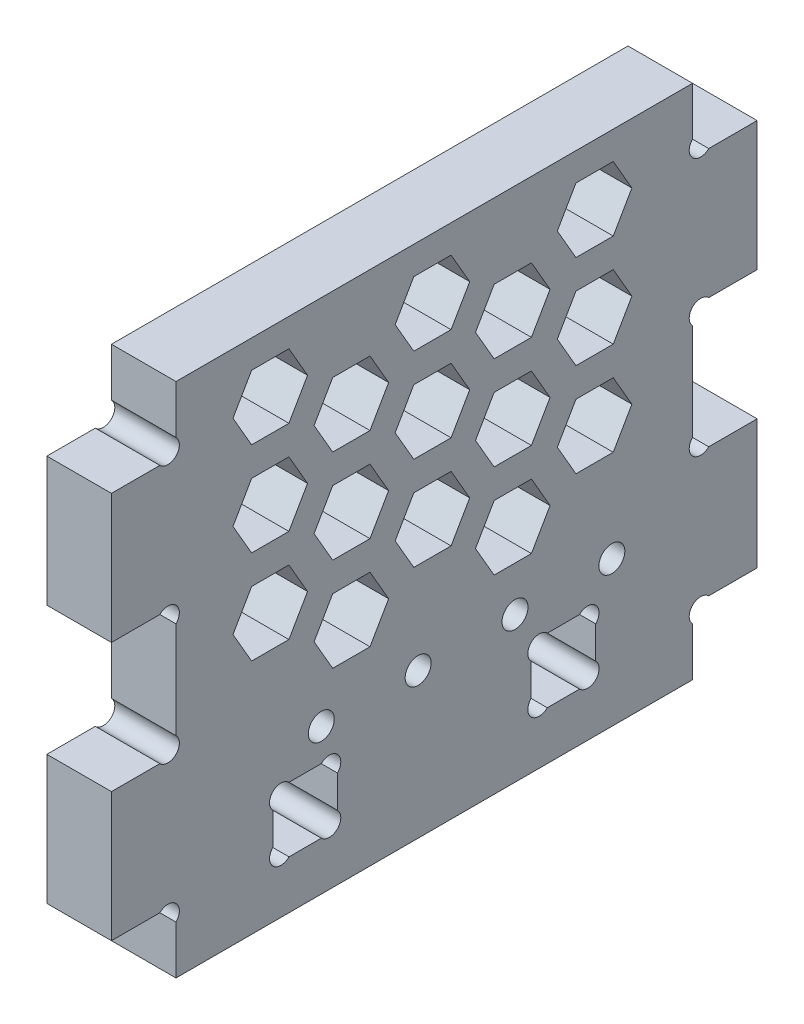
SolidWorks part; units mm, degrees
material "6061 Alloy"
ref_plane "Front" through (0, 0, 0) normal (0, 0, 1) x (1, 0, 0)
ref_plane "Top" through (0, 0, 0) normal (0, 1, 0) x (1, 0, 0)
ref_plane "Right" through (0, 0, 0) normal (1, 0, 0) x (0, 0, -1)
sketch "Sketch3" plane through (0, 0, 0) normal (1, 0, 0) x (0, 0, -1)
  line L1 (-50.8, -50.8) -> (50.8, -50.8)
  line L2 (-50.8, -50.8) -> (-50.8, 50.8)
  line L3 (-50.8, 50.8) -> (50.8, 50.8)
  line L4 (50.8, -50.8) -> (50.8, 50.8)
  line L5 (-50.8, -50.8) -> (50.8, 50.8) construction
  line L6 (-50.8, 50.8) -> (50.8, -50.8) construction
  point P0 (0, 0)
  dimension "D1" = 101.6
  dimension "D2" = 101.6
extrude "Square Extrusion" add sketch "Sketch3" along normal blind 12.7
sketch "Sketch4" plane through (12.7, 0, 0) normal (1, 0, 0) x (0, 0, -1)
  line L0 (-50.8, -50.8) -> (-25.4, -50.8) construction
  line L1 (-50.8, -50.8) -> (50.8, -50.8) construction
  line L2 (-25.4, -50.8) -> (-25.4, -34.925) construction
  line L3 (0, -50.8) -> (0, 50.8) construction
  line L4 (-31.75, -41.275) -> (-19.05, -41.275)
  line L5 (-31.75, -41.275) -> (-31.75, -28.575)
  line L6 (-31.75, -28.575) -> (-19.05, -28.575)
  line L7 (-19.05, -41.275) -> (-19.05, -28.575)
  line L8 (-31.75, -41.275) -> (-19.05, -28.575) construction
  line L9 (-31.75, -28.575) -> (-19.05, -41.275) construction
  line L10 (50.8, 50.8) -> (-50.8, 50.8) construction
  line L11 (31.75, -28.575) -> (19.05, -28.575)
  line L12 (19.05, -41.275) -> (19.05, -28.575)
  line L13 (31.75, -41.275) -> (19.05, -41.275)
  line L14 (31.75, -41.275) -> (31.75, -28.575)
  line L15 (-31.75, -34.925) -> (-19.05, -34.925) construction
  circle A0 centre (-20.6375, -30.1625) radius 2.2454
  circle A1 centre (-30.1625, -30.1625) radius 2.2454
  circle A2 centre (-20.6375, -39.6875) radius 2.2454
  circle A3 centre (-30.1625, -39.6875) radius 2.2454
  circle A4 centre (30.1625, -39.6875) radius 2.2454
  circle A5 centre (20.6375, -39.6875) radius 2.2454
  circle A6 centre (20.6375, -30.1625) radius 2.2454
  circle A7 centre (30.1625, -30.1625) radius 2.2454
  dimension "D7" = 4.4907
  dimension "D1" = 25.4
  dimension "D2" = 9.525
  dimension "D3" = 12.7
  dimension "D4" = 12.7
  dimension "D5" = 1.5875
extrude "Slotting Holes" cut sketch "Sketch4" against normal up to surface (12.7 mm away) contours A1 L5 L6 | A1 L6 L5 | A3 L4 A2 L7 A0 L6 A1 L5 | L6 A0 L7 | L7 A0 L6 | L4 A3 L5 | L5 A3 L4 | A2 L4 L7 | A2 L7 L4 | A6 L12 L11 | A6 L11 L12 | A7 L11 A6 L12 A5 L13 A4 L14 | L11 A7 L14 | L14 A7 L11 | A4 L13 L14 | A4 L14 L13 | L13 A5 L12 | L12 A5 L13 up to face at (0, 0, 0)
sketch "Sketch9" plane through (12.7, 0, 0) normal (1, 0, 0) x (0, 0, -1)
  line L96 (0, 0) -> (0, 11.43) construction
  line L97 (0, 6.985) -> (0, -6.985) construction
  line L111 (6.9677, 38.9312) -> (3.3015, 45.2812)
  line L112 (-24.9281, 38.9312) -> (-28.5942, 45.2812)
  line L113 (-28.5942, 45.2812) -> (-35.9266, 45.2812)
  line L114 (-35.9266, 45.2812) -> (-39.5928, 38.9312)
  line L115 (-39.5928, 38.9312) -> (-35.9266, 32.5812)
  line L116 (-35.9266, 32.5812) -> (-28.5942, 32.5812)
  line L117 (-28.5942, 32.5812) -> (-24.9281, 38.9312)
  line L118 (3.3015, 45.2812) -> (-4.0309, 45.2812)
  line L119 (-4.0309, 45.2812) -> (-7.697, 38.9312)
  line L120 (-7.697, 38.9312) -> (-4.0309, 32.5812)
  line L121 (-4.0309, 32.5812) -> (3.3015, 32.5812)
  line L122 (3.3015, 32.5812) -> (6.9677, 38.9312)
  line L123 (38.8634, 38.9312) -> (35.1972, 45.2812)
  line L124 (35.1972, 45.2812) -> (27.8648, 45.2812)
  line L125 (27.8648, 45.2812) -> (24.1987, 38.9312)
  line L126 (24.1987, 38.9312) -> (27.8648, 32.5812)
  line L127 (27.8648, 32.5812) -> (35.1972, 32.5812)
  line L128 (35.1972, 32.5812) -> (38.8634, 38.9312)
  line L129 (-8.9802, 29.7237) -> (-12.6464, 36.0737)
  line L130 (-12.6464, 36.0737) -> (-19.9787, 36.0737)
  line L131 (-19.9787, 36.0737) -> (-23.6449, 29.7237)
  line L132 (-23.6449, 29.7237) -> (-19.9787, 23.3737)
  line L133 (-19.9787, 23.3737) -> (-12.6464, 23.3737)
  line L134 (-12.6464, 23.3737) -> (-8.9802, 29.7237)
  line L135 (22.7698, 29.7237) -> (19.1036, 36.0737)
  line L136 (19.1036, 36.0737) -> (11.7713, 36.0737)
  line L137 (11.7713, 36.0737) -> (8.1051, 29.7237)
  line L138 (8.1051, 29.7237) -> (11.7713, 23.3737)
  line L139 (11.7713, 23.3737) -> (19.1036, 23.3737)
  line L140 (19.1036, 23.3737) -> (22.7698, 29.7237)
  line L141 (-24.9281, 20.5162) -> (-28.5942, 26.8662)
  line L142 (-28.5942, 26.8662) -> (-35.9266, 26.8662)
  line L143 (-35.9266, 26.8662) -> (-39.5928, 20.5162)
  line L144 (-39.5928, 20.5162) -> (-35.9266, 14.1662)
  line L145 (-35.9266, 14.1662) -> (-28.5942, 14.1662)
  line L146 (-28.5942, 14.1662) -> (-24.9281, 20.5162)
  line L147 (6.9677, 20.5162) -> (3.3015, 26.8662)
  line L148 (3.3015, 26.8662) -> (-4.0309, 26.8662)
  line L149 (-4.0309, 26.8662) -> (-7.697, 20.5162)
  line L150 (-7.697, 20.5162) -> (-4.0309, 14.1662)
  line L151 (-4.0309, 14.1662) -> (3.3015, 14.1662)
  line L152 (3.3015, 14.1662) -> (6.9677, 20.5162)
  line L153 (38.8634, 20.5162) -> (35.1972, 26.8662)
  line L154 (35.1972, 26.8662) -> (27.8648, 26.8662)
  line L155 (27.8648, 26.8662) -> (24.1987, 20.5162)
  line L156 (24.1987, 20.5162) -> (27.8648, 14.1662)
  line L157 (27.8648, 14.1662) -> (35.1972, 14.1662)
  line L158 (35.1972, 14.1662) -> (38.8634, 20.5162)
  line L159 (-24.9281, 2.1012) -> (-28.5942, 8.4512)
  line L160 (-28.5942, 8.4512) -> (-35.9266, 8.4512)
  line L161 (-35.9266, 8.4512) -> (-39.5928, 2.1012)
  line L162 (-39.5928, 2.1012) -> (-35.9266, -4.2488)
  line L163 (-35.9266, -4.2488) -> (-28.5942, -4.2488)
  line L164 (-28.5942, -4.2488) -> (-24.9281, 2.1012)
  line L165 (-8.9802, -7.1063) -> (-12.6464, -0.7563)
  line L166 (-12.6464, -0.7563) -> (-19.9787, -0.7563)
  line L167 (-19.9787, -0.7563) -> (-23.6449, -7.1063)
  line L168 (-23.6449, -7.1063) -> (-19.9787, -13.4563)
  line L169 (-19.9787, -13.4563) -> (-12.6464, -13.4563)
  line L170 (-12.6464, -13.4563) -> (-8.9802, -7.1063)
  line L171 (6.9677, 2.1012) -> (3.3015, 8.4512)
  line L172 (3.3015, 8.4512) -> (-4.0309, 8.4512)
  line L173 (-4.0309, 8.4512) -> (-7.697, 2.1012)
  line L174 (-7.697, 2.1012) -> (-4.0309, -4.2488)
  line L175 (-4.0309, -4.2488) -> (3.3015, -4.2488)
  line L176 (3.3015, -4.2488) -> (6.9677, 2.1012)
  line L177 (22.7698, -7.1063) -> (19.1036, -0.7563)
  line L178 (19.1036, -0.7563) -> (11.7713, -0.7563)
  line L179 (11.7713, -0.7563) -> (8.1051, -7.1063)
  line L180 (8.1051, -7.1063) -> (11.7713, -13.4563)
  line L181 (11.7713, -13.4563) -> (19.1036, -13.4563)
  line L182 (19.1036, -13.4563) -> (22.7698, -7.1063)
  line L183 (38.8634, 2.1012) -> (35.1972, 8.4512)
  line L184 (35.1972, 8.4512) -> (27.8648, 8.4512)
  line L185 (27.8648, 8.4512) -> (24.1987, 2.1012)
  line L186 (24.1987, 2.1012) -> (27.8648, -4.2488)
  line L187 (27.8648, -4.2488) -> (35.1972, -4.2488)
  line L188 (35.1972, -4.2488) -> (38.8634, 2.1012)
  line L189 (38.8634, -16.3138) -> (35.1972, -9.9638)
  line L190 (35.1972, -9.9638) -> (27.8648, -9.9638)
  line L191 (27.8648, -9.9638) -> (24.1987, -16.3138)
  line L192 (24.1987, -16.3138) -> (27.8648, -22.6638)
  line L193 (27.8648, -22.6638) -> (35.1972, -22.6638)
  line L194 (35.1972, -22.6638) -> (38.8634, -16.3138)
  line L195 (6.9677, -16.3138) -> (3.3015, -9.9638)
  line L196 (-4.0309, -9.9638) -> (-7.697, -16.3138)
  line L197 (-7.697, -16.3138) -> (-4.0309, -22.6638)
  line L198 (-4.0309, -22.6638) -> (3.3015, -22.6638)
  line L199 (3.3015, -22.6638) -> (6.9677, -16.3138)
  line L200 (3.3015, -9.9638) -> (-4.0309, -9.9638)
  line L201 (-24.9281, -16.3138) -> (-28.5942, -9.9638)
  line L202 (-28.5942, -9.9638) -> (-35.9266, -9.9638)
  line L203 (-35.9266, -9.9638) -> (-39.5928, -16.3138)
  line L204 (-39.5928, -16.3138) -> (-35.9266, -22.6638)
  line L205 (-35.9266, -22.6638) -> (-28.5942, -22.6638)
  line L206 (-28.5942, -22.6638) -> (-24.9281, -16.3138)
  line L207 (22.7698, 11.3087) -> (19.1036, 17.6587)
  line L208 (19.1036, 17.6587) -> (11.7713, 17.6587)
  line L209 (11.7713, 17.6587) -> (8.1051, 11.3087)
  line L210 (8.1051, 11.3087) -> (11.7713, 4.9587)
  line L211 (11.7713, 4.9587) -> (19.1036, 4.9587)
  line L212 (19.1036, 4.9587) -> (22.7698, 11.3087)
  line L213 (-8.9802, 11.3087) -> (-12.6464, 17.6587)
  line L214 (-12.6464, 17.6587) -> (-19.9787, 17.6587)
  line L215 (-19.9787, 17.6587) -> (-23.6449, 11.3087)
  line L216 (-23.6449, 11.3087) -> (-19.9787, 4.9587)
  line L217 (-19.9787, 4.9587) -> (-12.6464, 4.9587)
  line L218 (-12.6464, 4.9587) -> (-8.9802, 11.3087)
  circle A0 centre (-32.2604, 38.9312) radius 6.35 construction
  circle A1 centre (-0.3647, 38.9312) radius 6.35 construction
  circle A2 centre (31.531, 38.9312) radius 6.35 construction
  circle A3 centre (-16.3126, 29.7237) radius 6.35 construction
  circle A4 centre (15.4374, 29.7237) radius 6.35 construction
  circle A5 centre (-32.2604, 20.5162) radius 6.35 construction
  circle A6 centre (-0.3647, 20.5162) radius 6.35 construction
  circle A7 centre (31.531, 20.5162) radius 6.35 construction
  circle A8 centre (-32.2604, 2.1012) radius 6.35 construction
  circle A9 centre (-16.3126, -7.1063) radius 6.35 construction
  circle A10 centre (-0.3647, 2.1012) radius 6.35 construction
  circle A11 centre (15.4374, -7.1063) radius 6.35 construction
  circle A12 centre (31.531, 2.1012) radius 6.35 construction
  circle A13 centre (31.531, -16.3138) radius 6.35 construction
  circle A14 centre (-0.3647, -16.3138) radius 6.35 construction
  circle A15 centre (-32.2604, -16.3138) radius 6.35 construction
  circle A16 centre (-16.3126, 11.3087) radius 6.35 construction
  circle A17 centre (15.4374, 11.3087) radius 6.35 construction
  dimension "D1" = 11.43
extrude "Honeycomb Pocketing" cut sketch "Sketch9" against normal up to surface (12.7 mm away) contours L116 L117 L112 L113 L114 L115 | L121 L122 L111 L118 L119 L120 | L127 L128 L123 L124 L125 L126 | L133 L134 L129 L130 L131 L132 | L139 L140 L135 L136 L137 L138 | L157 L158 L153 L154 L155 L156 | L151 L152 L147 L148 L149 L150 | L145 L146 L141 L142 L143 L144 | L217 L218 L213 L214 L215 L216 | L211 L212 L207 L208 L209 L210 | L163 L164 L159 L160 L161 L162 | L175 L176 L171 L172 L173 L174 | L187 L188 L183 L184 L185 L186 | L169 L170 L165 L166 L167 L168 | L181 L182 L177 L178 L179 L180 up to face at (0, -34.925, 25.4)
sketch "Sketch10" plane through (12.7, 0, 0) normal (1, 0, 0) x (0, 0, -1)
  line L0 (-50.8, 0) -> (50.8, 0) construction
  line L1 (-50.8, 0) -> (-50.8, 50.8) construction
  line L2 (-50.8, 25.4) -> (-63.5, 25.4)
  line L3 (-50.8, 25.4) -> (-50.8, 38.1)
  line L4 (-50.8, 38.1) -> (-63.5, 38.1)
  line L5 (-63.5, 25.4) -> (-63.5, 38.1)
  line L6 (-63.5, 25.4) -> (-50.8, 25.4)
  line L7 (-63.5, 25.4) -> (-63.5, 12.7)
  line L8 (-63.5, 12.7) -> (-50.8, 12.7)
  line L9 (-50.8, 25.4) -> (-50.8, 12.7)
  line L10 (50.8, -50.8) -> (50.8, 50.8) construction
  line L11 (-63.5, -12.7) -> (-50.8, -12.7)
  line L12 (-50.8, -25.4) -> (-50.8, -12.7)
  line L13 (-63.5, -25.4) -> (-50.8, -25.4)
  line L14 (-63.5, -25.4) -> (-63.5, -12.7)
  line L15 (-50.8, -38.1) -> (-63.5, -38.1)
  line L16 (-63.5, -25.4) -> (-63.5, -38.1)
  line L17 (-50.8, -25.4) -> (-63.5, -25.4)
  line L18 (-50.8, -25.4) -> (-50.8, -38.1)
  line L19 (0, 50.8) -> (0, -50.8) construction
  line L20 (50.8, 50.8) -> (-50.8, 50.8) construction
  line L21 (-50.8, -50.8) -> (50.8, -50.8) construction
  line L22 (50.8, -38.1) -> (63.5, -38.1)
  line L23 (63.5, -25.4) -> (63.5, -38.1)
  line L24 (63.5, -25.4) -> (50.8, -25.4)
  line L25 (63.5, -25.4) -> (63.5, -12.7)
  line L26 (63.5, -12.7) -> (50.8, -12.7)
  line L27 (50.8, -25.4) -> (50.8, -12.7)
  line L28 (50.8, -25.4) -> (50.8, -38.1)
  line L29 (63.5, 12.7) -> (50.8, 12.7)
  line L30 (50.8, 25.4) -> (50.8, 12.7)
  line L31 (63.5, 25.4) -> (50.8, 25.4)
  line L32 (63.5, 25.4) -> (63.5, 12.7)
  line L33 (50.8, 38.1) -> (63.5, 38.1)
  line L34 (63.5, 25.4) -> (63.5, 38.1)
  line L35 (50.8, 25.4) -> (63.5, 25.4)
  line L36 (50.8, 25.4) -> (50.8, 38.1)
  line L37 (-63.5, 38.1) -> (-50.8, 38.1)
  line L43 (-63.5, 12.7) -> (-50.8, 12.7)
  line L44 (-53.9752, 41.2752) -> (-50.8, 38.1) construction
  line L46 (-50.8, 41.2754) -> (-50.8, 38.1)
  line L47 (-50.8, 12.7) -> (-50.8, 9.5246)
  line L48 (-50.8, -9.5246) -> (-50.8, -12.7)
  line L49 (-50.8, 50.8) -> (-50.8, -50.8) construction
  line L50 (-50.8, -41.2754) -> (-50.8, -38.1)
  line L51 (50.8, -41.2754) -> (50.8, -38.1)
  line L52 (50.8, -9.5246) -> (50.8, -12.7)
  line L53 (50.8, 12.7) -> (50.8, 9.5246)
  line L54 (50.8, 41.2754) -> (50.8, 38.1)
  arc A2 (-53.9754, 38.1) -> (-50.8, 41.2754) centre (-52.3877, 39.6877) ccw
  arc A5 (-53.9754, 12.7) -> (-50.8, 9.5246) centre (-52.3877, 11.1123) cw
  arc A8 (53.9754, 12.7) -> (50.8, 9.5246) centre (52.3877, 11.1123) ccw
  arc A9 (53.9754, 38.1) -> (50.8, 41.2754) centre (52.3877, 39.6877) cw
  arc A10 (53.9754, -12.7) -> (50.8, -9.5246) centre (52.3877, -11.1123) cw
  arc A11 (53.9754, -38.1) -> (50.8, -41.2754) centre (52.3877, -39.6877) ccw
  arc A12 (-53.9754, -12.7) -> (-50.8, -9.5246) centre (-52.3877, -11.1123) ccw
  arc A13 (-53.9754, -38.1) -> (-50.8, -41.2754) centre (-52.3877, -39.6877) cw
  point P43 (50.8, 50.8)
  point P68 (0, 0)
  dimension "D4" = 12.7
  dimension "D1" = 12.7
  dimension "D2" = 12.7
  dimension "D3" = 12.7
extrude "Side Slots" add sketch "Sketch10" against normal blind 12.7 contours L5 L2 L3 L4 | L9 L2 L7 L8 | L14 L13 L12 L11 | L18 L13 L16 L15 | L27 L24 L25 L26 | L24 L28 L22 L23 | L32 L31 L30 L29 | L36 L31 L34 L33
sketch "Sketch12" plane through (12.7, 0, 0) normal (1, 0, 0) x (0, 0, -1)
  circle A0 centre (-22.225, -22.225) radius 2.5527
  circle A1 centre (-3.175, -22.225) radius 2.5527
  circle A2 centre (15.875, -22.225) radius 2.5527
  circle A3 centre (34.925, -22.225) radius 2.5527
  circle A12 centre (-52.3877, 39.6877) radius 2.2454
  circle A13 centre (-52.3877, 11.1123) radius 2.2454
  circle A14 centre (-52.3877, -11.1123) radius 2.2454
  circle A15 centre (-52.3877, -39.6877) radius 2.2454
  circle A16 centre (52.3877, 39.6877) radius 2.2454
  circle A17 centre (52.3877, 11.1123) radius 2.2454
  circle A18 centre (52.3877, -11.1123) radius 2.2454
  circle A19 centre (52.3877, -39.6877) radius 2.2454
  point P0 (-50.8, -38.1)
  point P12 (50.8, 50.8)
extrude "Cut-Extrude1" cut sketch "Sketch12" against normal through all
